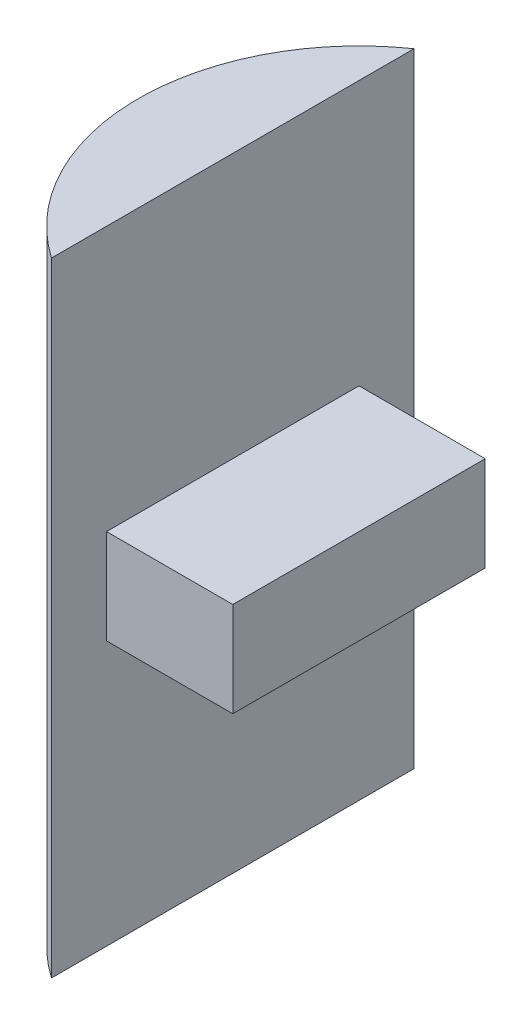
SolidWorks part; units mm, degrees
ref_plane "前视基准面" through (0, 0, 0) normal (0, 0, 1) x (1, 0, 0)
ref_plane "上视基准面" through (0, 0, 0) normal (0, 1, 0) x (1, 0, 0)
ref_plane "右视基准面" through (0, 0, 0) normal (1, 0, 0) x (0, 0, -1)
other "Configuration Table"
sketch "草图1" plane through (0, 0, 0) normal (0, 1, 0) x (1, 0, 0)
  circle A0 centre (0, 0) radius 2.5
  dimension "D1" = 5
extrude "凸台-拉伸1" add sketch "草图1" along normal blind 23.88
sketch "草图2" plane through (0, 0, 0) normal (0, 1, 0) x (1, 0, 0)
  line L0 (-1000, 0) -> (49000, 0) construction
  line L1 (0.1667, 2.4944) -> (7.6333, 1.9956)
  line L2 (0.1667, -2.4944) -> (7.6333, -1.9956)
  circle A0 centre (0, 0) radius 2.5 construction
  arc A1 (0.1667, 2.4944) -> (0.1667, -2.4944) centre (0, 0) ccw
  arc A2 (7.6333, -1.9956) -> (7.6333, 1.9956) centre (7.5, 0) ccw
  circle A3 centre (7.5, 0) radius 1
  dimension "D1" = 4
  dimension "D3" = 2
  dimension "D2" = 7.5
extrude "凸台-拉伸2" add sketch "草图2" along normal blind 1
sketch "草图3" plane through (0, 0, 0) normal (0, 1, 0) x (1, 0, 0)
  line L0 (-1000, 0) -> (49000, 0) construction
  line L1 (0, -1000) -> (0, 49000) construction
  line L4 (-1.854, -0.75) -> (-0.75, -0.75)
  line L6 (1.854, 0.75) -> (0.75, 0.75)
  line L7 (-0.75, 1.854) -> (-0.75, 0.75)
  line L9 (0.75, -1.854) -> (0.75, -0.75)
  line L10 (0.75, -0.75) -> (1.854, -0.75)
  line L11 (-0.75, -0.75) -> (-0.75, -1.854)
  line L12 (0.75, 0.75) -> (0.75, 1.854)
  line L13 (-0.75, 0.75) -> (-1.854, 0.75)
  arc A0 (-1.854, 0.75) -> (-1.854, -0.75) centre (0, 0) ccw
  arc A1 (0.75, 1.854) -> (-0.75, 1.854) centre (0, 0) ccw
  arc A2 (1.854, -0.75) -> (1.854, 0.75) centre (0, 0) ccw
  arc A3 (-0.75, -1.854) -> (0.75, -1.854) centre (0, 0) ccw
  point P10 (0, 1.854)
  point P13 (-1.854, 0)
  dimension "D1" = 4
  dimension "D2" = 1.5
  dimension "D3" = 1.5
  dimension "D4" = 1.104
  dimension "D5" = 2.1213
extrude "切除-拉伸1" cut sketch "草图3" along normal blind 5 contours L10 A2 L6 L12 A1 L7 L13 A0 L4 L11 L9
sketch "草图5" plane through (0, 0, 0) normal (0, 1, 0) x (1, 0, 0)
  line L0 (1.854, 0.75) -> (0.75, 0.75) construction
  line L1 (0.75, 0.75) -> (0.75, 1.854) construction
  line L2 (-0.75, 1.854) -> (-0.75, 0.75) construction
  line L3 (-0.75, 0.75) -> (-1.854, 0.75) construction
  line L4 (-0.75, -0.75) -> (-0.75, -1.854) construction
  line L5 (0.75, -1.854) -> (0.75, -0.75) construction
  line L6 (-1.854, -0.75) -> (-0.75, -0.75) construction
  line L7 (0.75, -0.75) -> (1.854, -0.75) construction
  line L8 (1.854, 0.75) -> (0.75, 0.75)
  line L9 (0.75, 0.75) -> (0.75, 1.854)
  line L10 (-0.75, 1.854) -> (-0.75, 0.75)
  line L11 (-0.75, 0.75) -> (-1.854, 0.75)
  line L12 (-0.75, -0.75) -> (-0.75, -1.854)
  line L13 (0.75, -1.854) -> (0.75, -0.75)
  line L14 (-1.854, -0.75) -> (-0.75, -0.75)
  line L15 (0.75, -0.75) -> (1.854, -0.75)
  arc A0 (0.75, 1.854) -> (-0.75, 1.854) centre (0, 0) ccw construction
  arc A1 (-1.854, 0.75) -> (-1.854, -0.75) centre (0, 0) ccw construction
  arc A2 (-0.75, -1.854) -> (0.75, -1.854) centre (0, 0) ccw construction
  arc A3 (1.854, -0.75) -> (1.854, 0.75) centre (0, 0) ccw construction
  arc A4 (0.75, 1.854) -> (-0.75, 1.854) centre (0, 0) ccw
  arc A5 (-1.854, 0.75) -> (-1.854, -0.75) centre (0, 0) ccw
  arc A6 (-0.75, -1.854) -> (0.75, -1.854) centre (0, 0) ccw
  arc A7 (1.854, -0.75) -> (1.854, 0.75) centre (0, 0) ccw
extrude "切除-拉伸2" cut sketch "草图5" against normal blind 5 from surface at 23.88 starting at face at (0, 23.88, 2.5)
sketch "草图6" plane through (0, 0, 0) normal (0, 1, 0) x (1, 0, 0)
  line L0 (0, 0) -> (0.75, 0) construction
  circle A0 centre (0.75, 0) radius 0.25
  dimension "D2" = 0.5
  dimension "D1" = 0.75
extrude "切除-拉伸3" cut sketch "草图6" against normal blind 0.25 from surface at 18.88 starting at face at (0, 18.88, 0)
sketch "草图7" plane through (0, 0, 0) normal (0, 1, 0) x (1, 0, 0)
  circle A0 centre (0.75, 0) radius 0.25 construction
  circle A1 centre (0.75, 0) radius 0.25
extrude "切除-拉伸4" cut sketch "草图7" along normal blind 0.25 from surface at 5 starting at face at (0, 5, 0)
sketch "草图17" plane through (0, 0, 0) normal (0, 1, 0) x (1, 0, 0)
  circle A0 centre (0, 0) radius 3.5
  dimension "D1" = 7
extrude "凸台-拉伸5" add sketch "草图17" along normal blind 9.88 from offset 7
sketch "草图20" plane through (0, 0, 0) normal (0, 0, 1) x (1, 0, 0)
  line L1 (-3.5, 16.88) -> (3.5, 16.88)
  line L2 (-3.5, 16.88) -> (-3.5, 7)
  line L3 (-3.5, 7) -> (3.5, 7)
  line L4 (3.5, 16.88) -> (3.5, 7)
extrude "切除-拉伸6" cut sketch "草图20" against normal through all and the other way through all flip side to cut
sketch "草图22" plane through (0, 0, 0) normal (0, 0, 1) x (1, 0, 0)
  line L0 (3.5, 16.88) -> (-3.5, 7) construction
  line L1 (3.5, 7) -> (-3.5, 16.88) construction
  line L2 (-3.5, 16.88) -> (-2, 16.88) construction
  line L3 (3.5, 16.88) -> (-3.5, 16.88) construction
  line L9 (-3.5, 7) -> (3.5, 7) construction
  line L10 (-2, 7) -> (3.5, 7)
  line L11 (3.5, 7) -> (3.5, 16.88)
  line L12 (3.5, 16.88) -> (-2, 16.88)
  line L17 (-2, 16.88) -> (-2, 7)
  point P25 (0, 11.94)
  dimension "D1" = 1.5
extrude "切除-拉伸7" cut sketch "草图22" against normal through all and the other way through all
sketch "草图24" plane through (0, 0, 0) normal (1, 0, 0) x (0, 0, -1)
  line L0 (2.8723, 16.88) -> (-2.8723, 7) construction
  line L1 (2.8723, 7) -> (-2.8723, 16.88) construction
  line L3 (-2, 12.69) -> (2, 12.69)
  line L4 (-2, 12.69) -> (-2, 11.19)
  line L5 (-2, 11.19) -> (2, 11.19)
  line L6 (2, 12.69) -> (2, 11.19)
  line L7 (-2, 12.69) -> (2, 11.19) construction
  line L8 (-2, 11.19) -> (2, 12.69) construction
  point P8 (0, 11.94)
  dimension "D1" = 1.5
  dimension "D2" = 4
extrude "凸台-拉伸6" add sketch "草图24" along normal blind 2 from surface at -2 contours L4 L3 L6 L5 starting at face at (-2, 11.94, 0)
